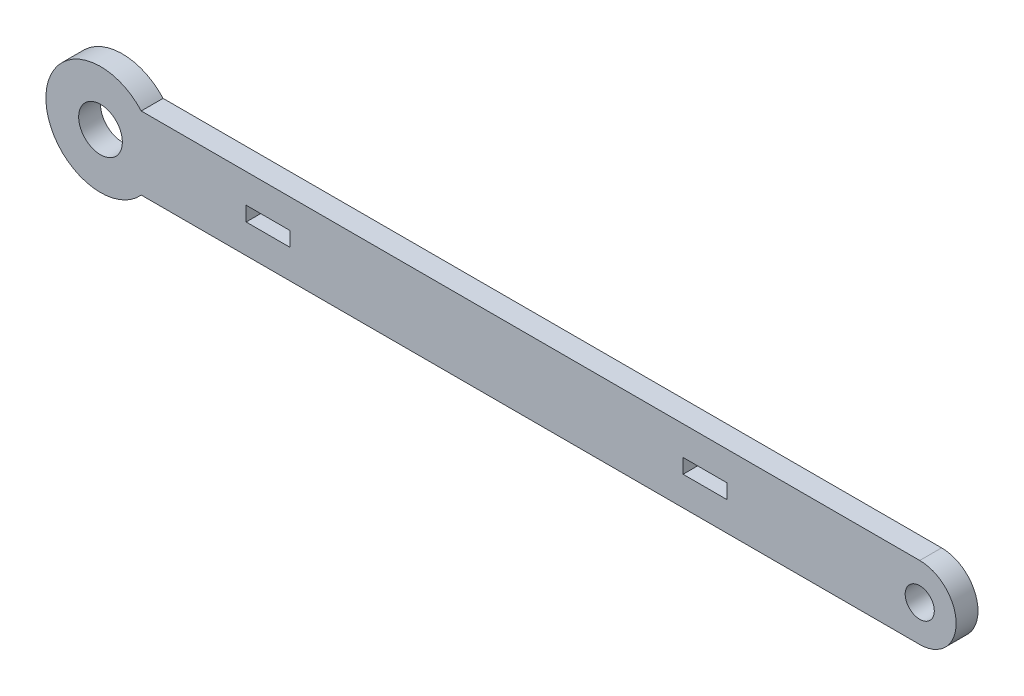
SolidWorks part; units mm, degrees
ref_plane "前视基准面" through (0, 0, 0) normal (0, 0, 1) x (1, 0, 0)
ref_plane "上视基准面" through (0, 0, 0) normal (0, 1, 0) x (1, 0, 0)
ref_plane "右视基准面" through (0, 0, 0) normal (1, 0, 0) x (0, 0, -1)
sketch "草图1" plane through (0, 0, 0) normal (0, 0, 1) x (1, 0, 0)
  line L0 (0, 0) -> (112.5, 0) construction
  line L1 (1.65, 0) -> (-1.65, 0) construction
  line L2 (5.5902, 5) -> (112.5, 5)
  line L3 (5.5902, -5) -> (112.5, -5)
  line L4 (20, 1) -> (20, -1)
  line L5 (20, -1) -> (26, -1)
  line L6 (26, -1) -> (26, 1)
  line L7 (26, 1) -> (20, 1)
  line L8 (80, 1) -> (80, -1)
  line L9 (80, -1) -> (86, -1)
  line L10 (86, -1) -> (86, 1)
  line L11 (86, 1) -> (80, 1)
  arc A1 (112.5, -5) -> (112.5, 5) centre (112.5, 0) ccw
  circle A2 centre (112.5, 0) radius 2
  circle A3 centre (0, 0) radius 3
  arc A4 (5.5902, 5) -> (5.5902, -5) centre (0, 0) ccw
  point P5 (56.25, 0)
extrude "凸台-拉伸1" add sketch "草图1" along normal mid plane 3
